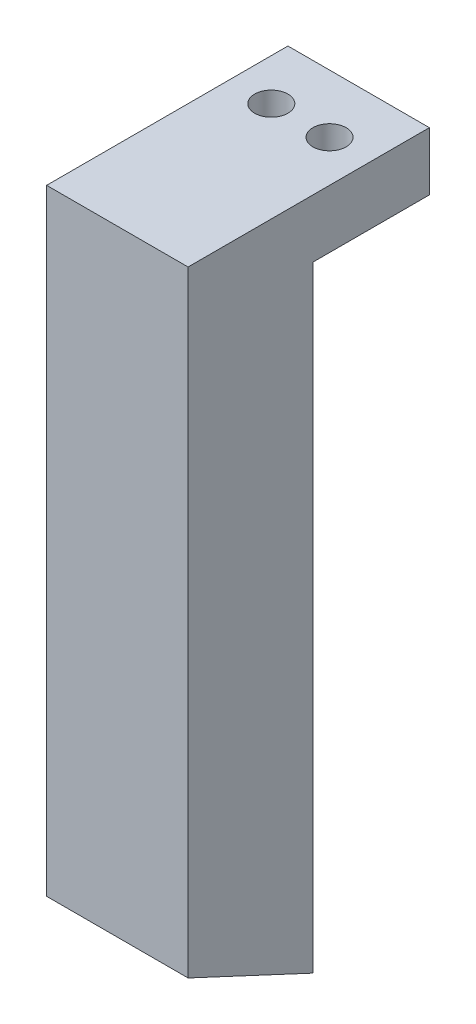
SolidWorks part; units mm, degrees
material "ABS"
ref_plane "Front Plane" through (0, 0, 0) normal (0, 0, 1) x (1, 0, 0)
ref_plane "Top Plane" through (0, 0, 0) normal (0, 1, 0) x (1, 0, 0)
ref_plane "Right Plane" through (0, 0, 0) normal (1, 0, 0) x (0, 0, -1)
sketch "Sketch1" plane through (0, 0, 0) normal (0, 1, 0) x (1, 0, 0)
  line L1 (-76.9048, 16.0714) -> (-59.9048, 16.0714)
  line L2 (-76.9048, 16.0714) -> (-76.9048, 1.0714)
  line L3 (-76.9048, 1.0714) -> (-59.9048, 1.0714)
  line L4 (-59.9048, 16.0714) -> (-59.9048, 1.0714)
  dimension "D1" = 15
  dimension "D2" = 17
extrude "Boss-Extrude1" add sketch "Sketch1" along normal blind 81
sketch "Sketch2" plane through (-59.9048, 0, 0) normal (1, 0, 0) x (0, 0, -1)
  line L3 (1.0714, 0) -> (16.0714, 0) construction
  line L5 (16.0714, 0) -> (1.0714, 0)
  line L6 (16.0714, 81) -> (16.0714, 0) construction
  line L7 (1.0714, 81) -> (1.0714, 0) construction
  line L8 (1.0714, 0) -> (1.0714, 6.9946)
  line L9 (1.0714, 6.9946) -> (16.0714, 0)
  dimension "D1" = 25
  dimension "D2" = 0
extrude "Cut-Extrude1" cut sketch "Sketch2" against normal blind 40
sketch "Sketch3" plane through (0, 6.1557, -2.8705) normal (0, -0.9063, 0.4226) x (1, 0, 0)
  line L0 (-76.9048, 1.985) -> (-59.9048, 1.985) construction
  line L1 (-59.9048, -14.5657) -> (-59.9048, 1.985) construction
  circle A0 centre (-68.4048, -5.515) radius 1.5
  point P4 (-68.4048, 1.985)
  dimension "D1" = 7.5
  dimension "D2" = 8.5
  dimension "D3" = 3
extrude "Cut-Extrude2" cut sketch "Sketch3" against normal blind 36
sketch "Sketch4" plane through (0, 0, -16.0714) normal (0, 0, -1) x (-1, 0, 0)
  line L0 (59.9048, 81) -> (59.9048, 0) construction
  line L1 (76.9048, 81) -> (59.9048, 81)
  line L2 (76.9048, 81) -> (76.9048, 74)
  line L3 (76.9048, 74) -> (59.9048, 74)
  line L4 (59.9048, 81) -> (59.9048, 74)
  dimension "D1" = 7
extrude "Boss-Extrude2" add sketch "Sketch4" along normal blind 14
sketch "Sketch5" plane through (0, 74, 0) normal (0, -1, 0) x (-1, 0, 0)
  line L0 (59.9048, 30.0714) -> (76.9048, 30.0714) construction
  line L1 (59.9048, 30.0714) -> (59.9048, 16.0714) construction
  line L2 (76.9048, 30.0714) -> (76.9048, 16.0714) construction
  circle A0 centre (71.9048, 23.0714) radius 2
  circle A1 centre (64.9048, 23.0714) radius 2
  dimension "D1" = 4
  dimension "D2" = 4
  dimension "D3" = 7
  dimension "D4" = 5
  dimension "D5" = 5
  dimension "D6" = 7
extrude "Cut-Extrude3" cut sketch "Sketch5" against normal blind 14
